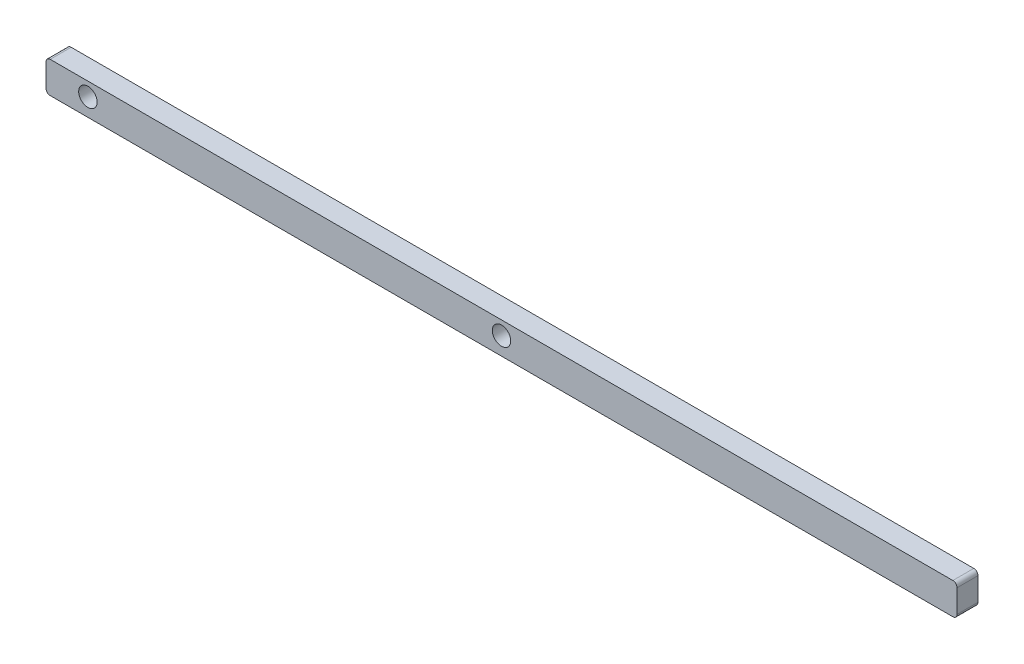
SolidWorks part; units mm, degrees
material "Balsa"
ref_plane "Front Plane" through (0, 0, 0) normal (0, 0, 1) x (1, 0, 0)
ref_plane "Top Plane" through (0, 0, 0) normal (0, 1, 0) x (1, 0, 0)
ref_plane "Right Plane" through (0, 0, 0) normal (1, 0, 0) x (0, 0, -1)
sketch "Sketch1" plane through (0, 0, 0) normal (0, 0, 1) x (1, 0, 0)
  line L1 (-276.225, -10.7829) -> (276.225, -10.7829)
  line L2 (-276.225, -10.7829) -> (-276.225, 8.2671)
  line L3 (-276.225, 8.2671) -> (276.225, 8.2671)
  line L4 (276.225, -10.7829) -> (276.225, 8.2671)
  circle A0 centre (0, 0) radius 5.588
  circle A1 centre (-250.825, 0) radius 5.588
  point P0 (0, 0)
  point P12 (0, 0)
  point P13 (0, 0)
  dimension "D3" = 11.176
  dimension "D4" = 11.176
  dimension "D1" = 552.45
  dimension "D2" = 19.05
  dimension "D6" = 25.4
extrude "Boss-Extrude1" add sketch "Sketch1" along normal mid plane 12.7
fillet "Fillet1" radius 2.54 4 edges at (-276.225, 8.2671, 0) (-276.225, -10.7829, 0) (276.225, -10.7829, 0) (276.225, 8.2671, 0)
